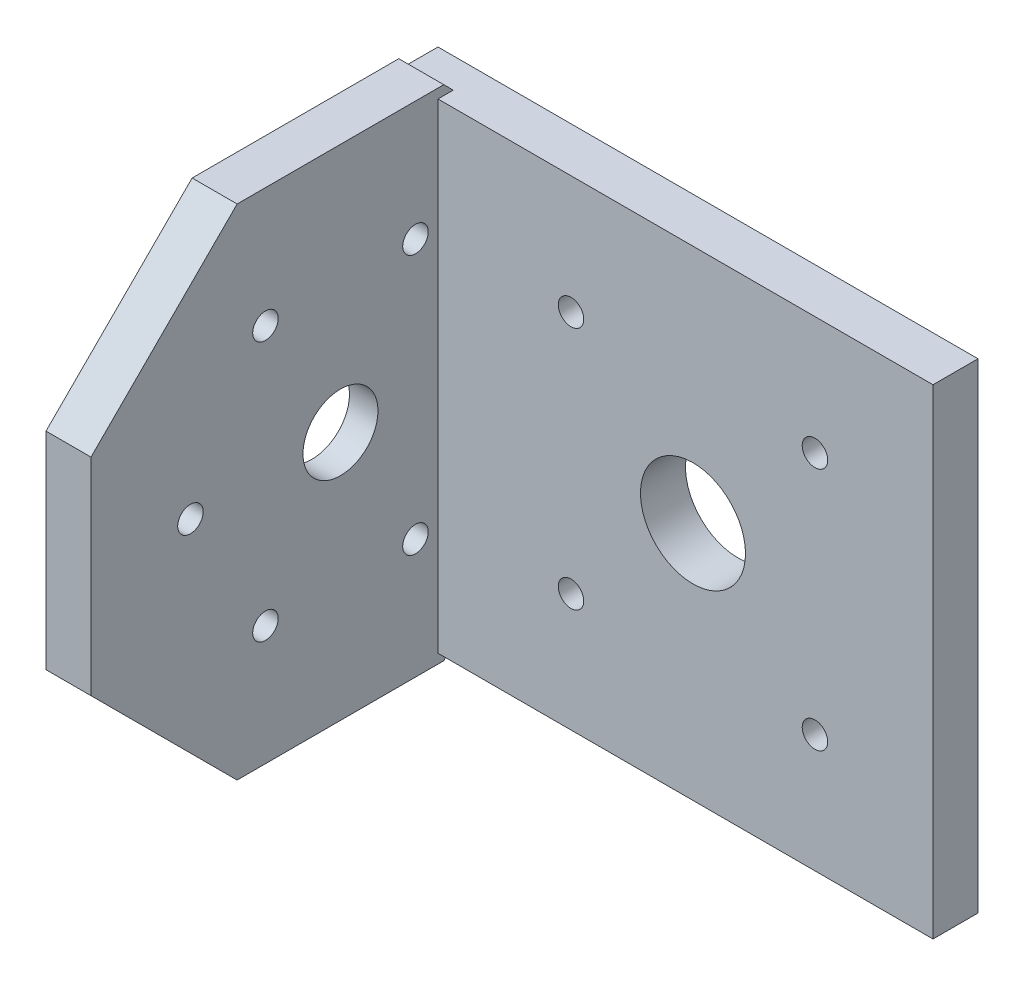
SolidWorks part; units mm, degrees
ref_plane "Front Plane" through (0, 0, 0) normal (0, 0, 1) x (1, 0, 0)
ref_plane "Top Plane" through (0, 0, 0) normal (0, 1, 0) x (1, 0, 0)
ref_plane "Right Plane" through (0, 0, 0) normal (1, 0, 0) x (0, 0, -1)
ref_plane "PL_Roll_Plate_base" through (-40, 0, 0) normal (1, 0, 0) x (0, 0, -1)
sketch "SK_Roll_Plate" plane through (-40, 0, 0) normal (1, 0, 0) x (0, 0, -1)
  line L0 (-13.7766, -33.2597) -> (-33.2597, -13.7766)
  line L1 (-33.2597, -13.7766) -> (-33.2597, 13.7766)
  line L2 (-33.2597, 13.7766) -> (-13.7766, 33.2597)
  line L3 (-13.7766, 33.2597) -> (13.7766, 33.2597)
  line L4 (13.7766, 33.2597) -> (33.2597, 13.7766)
  line L5 (33.2597, 13.7766) -> (33.2597, -13.7766)
  line L6 (33.2597, -13.7766) -> (13.7766, -33.2597)
  line L7 (13.7766, -33.2597) -> (-13.7766, -33.2597)
  circle A0 centre (20, 0) radius 1.7
  circle A1 centre (10, -17.3205) radius 1.7
  circle A2 centre (-10, -17.3205) radius 1.7
  circle A3 centre (-20, 0) radius 1.7
  circle A4 centre (-10, 17.3205) radius 1.7
  circle A5 centre (10, 17.3205) radius 1.7
  circle A6 centre (0, 0) radius 5
  dimension "D17_SK_Roll_Plate" = 3.4
  dimension "D19_SK_Roll_Plate" = 3.4
  dimension "D22_SK_Roll_Plate" = 3.4
  dimension "D25_SK_Roll_Plate" = 3.4
  dimension "D27_SK_Roll_Plate" = 3.4
  dimension "D30_SK_Roll_Plate" = 3.4
  dimension "D33_SK_Roll_Plate" = 10
  dimension "P1" = 13.7766
  dimension "P2" = 33.2597
  dimension "P3" = 33.2597
  dimension "P4" = 13.7766
  dimension "P5" = 33.2597
  dimension "P6" = 13.7766
  dimension "P7" = 13.7766
  dimension "P8" = 33.2597
  dimension "P9" = 13.7766
  dimension "P10" = 33.2597
  dimension "P11" = 33.2597
  dimension "P12" = 13.7766
  dimension "P13" = 33.2597
  dimension "P14" = 13.7766
  dimension "P15" = 13.7766
  dimension "P16" = 33.2597
  dimension "P18" = 20
  dimension "P20" = 10
  dimension "P21" = 17.3205
  dimension "P23" = 10
  dimension "P24" = 17.3205
  dimension "P26" = 20
  dimension "P28" = 10
  dimension "P29" = 17.3205
  dimension "P31" = 10
  dimension "P32" = 17.3205
extrude "Roll_Plate" add sketch "SK_Roll_Plate" along normal blind 6
ref_plane "PL_Yaw_Plate_base" through (0, 0, -19) normal (0, 0, 1) x (1, 0, 0)
sketch "SK_Yaw_Plate" plane through (0, 0, -19) normal (0, 0, 1) x (1, 0, 0)
  line L0 (-40, 32) -> (32, 32)
  line L1 (32, 32) -> (32, -32)
  line L2 (32, -32) -> (-40, -32)
  line L3 (-40, -32) -> (-40, 32)
  circle A0 centre (16.2635, -16.2635) radius 1.7
  circle A1 centre (-16.2635, -16.2635) radius 1.7
  circle A2 centre (-16.2635, 16.2635) radius 1.7
  circle A3 centre (16.2635, 16.2635) radius 1.7
  circle A4 centre (0, 0) radius 7
  dimension "D9_SK_Yaw_Plate" = 3.4
  dimension "D12_SK_Yaw_Plate" = 3.4
  dimension "D15_SK_Yaw_Plate" = 3.4
  dimension "D18_SK_Yaw_Plate" = 3.4
  dimension "D21_SK_Yaw_Plate" = 14
  dimension "P1" = 40
  dimension "P2" = 32
  dimension "P3" = 32
  dimension "P4" = 32
  dimension "P5" = 32
  dimension "P6" = 32
  dimension "P7" = 40
  dimension "P8" = 32
  dimension "P10" = 16.2635
  dimension "P11" = 16.2635
  dimension "P13" = 16.2635
  dimension "P14" = 16.2635
  dimension "P16" = 16.2635
  dimension "P17" = 16.2635
  dimension "P19" = 16.2635
  dimension "P20" = 16.2635
extrude "Yaw_Plate" add sketch "SK_Yaw_Plate" along normal blind 6
ref_plane "PL_Roll_Pilot_Recess_base" through (-40, 0, 0) normal (1, 0, 0) x (0, 0, -1)
sketch "SK_Roll_Pilot_Recess" plane through (-40, 0, 0) normal (1, 0, 0) x (0, 0, -1)
  circle A0 centre (0, 0) radius 15.15
  dimension "D1_SK_Roll_Pilot_Recess" = 30.3
extrude "Roll_Pilot_Recess" cut sketch "SK_Roll_Pilot_Recess" along normal blind 2.2
equation "\"Roll_face_x\" = -40"
equation "\"Yaw_rear_z\" = -19"
